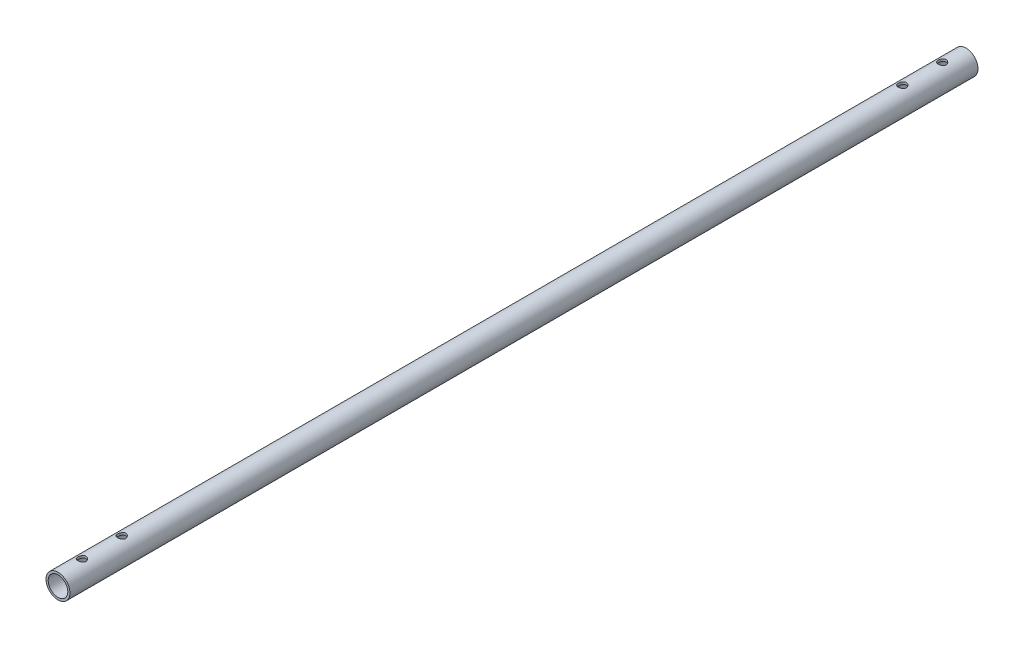
SolidWorks part; units mm, degrees
material "CK45"
ref_plane "Front Plane" through (0, 0, 0) normal (0, 0, 1) x (1, 0, 0)
ref_plane "Top Plane" through (0, 0, 0) normal (0, 1, 0) x (1, 0, 0)
ref_plane "Right Plane" through (0, 0, 0) normal (1, 0, 0) x (0, 0, -1)
sketch "Sketch1" plane through (0, 0, 0) normal (0, 0, 1) x (1, 0, 0)
  circle A0 centre (0, 0) radius 30.15
  dimension "D1" = 60.3
extrude "Extrude-Thin1" add sketch "Sketch1" along normal mid plane 2280 thin thin type one direction reverse wall 5.54
sketch "Sketch2" plane through (0, 0, 0) normal (0, 1, 0) x (1, 0, 0)
  line L0 (24.61, 1140) -> (-24.61, 1140) construction
  line L1 (0, 1140) -> (0, 699.6614) construction
  line L2 (30.15, 1140) -> (-30.15, 1140) construction
  circle A0 centre (0, 1080) radius 10.05
  circle A1 centre (0, 980) radius 10.05
  dimension "D1" = 20.1
  dimension "D2" = 60
  dimension "D3" = 100
extrude "Cut-Extrude1" cut sketch "Sketch2" against normal through all both and the other way through all
mirror "Mirror1" about plane through (0, 0, 0) normal (0, 0, 1) of "Cut-Extrude1"
